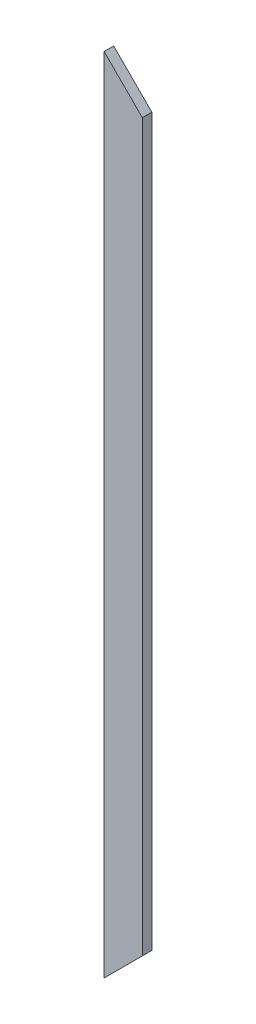
SolidWorks part; units mm, degrees
ref_plane "Plan de face" through (0, 0, 0) normal (0, 0, 1) x (1, 0, 0)
ref_plane "Plan de dessus" through (0, 0, 0) normal (0, 1, 0) x (1, 0, 0)
ref_plane "Plan de droite" through (0, 0, 0) normal (1, 0, 0) x (0, 0, -1)
sketch "Esquisse1" plane through (0, 0, 0) normal (0, 0, 1) x (1, 0, 0)
  line L0 (0, 0) -> (10, 0)
  line L1 (10, 0) -> (10, -200) construction
  line L2 (10, -200) -> (0, -210)
  line L3 (0, -210) -> (0, 0)
  line L4 (10, 0) -> (20, 0)
  line L5 (20, 0) -> (20, -190)
  line L6 (20, -190) -> (10, -200)
  dimension "D1" = 10
  dimension "D2" = 45
  dimension "D3" = 200
  dimension "D4" = 10
extrude "Boss.-Extru.1" add sketch "Esquisse1" along normal blind 5
mirror "Symétrie1" about plane through (0, 0, 5) normal (0, -1, 0) of "Boss.-Extru.1"
